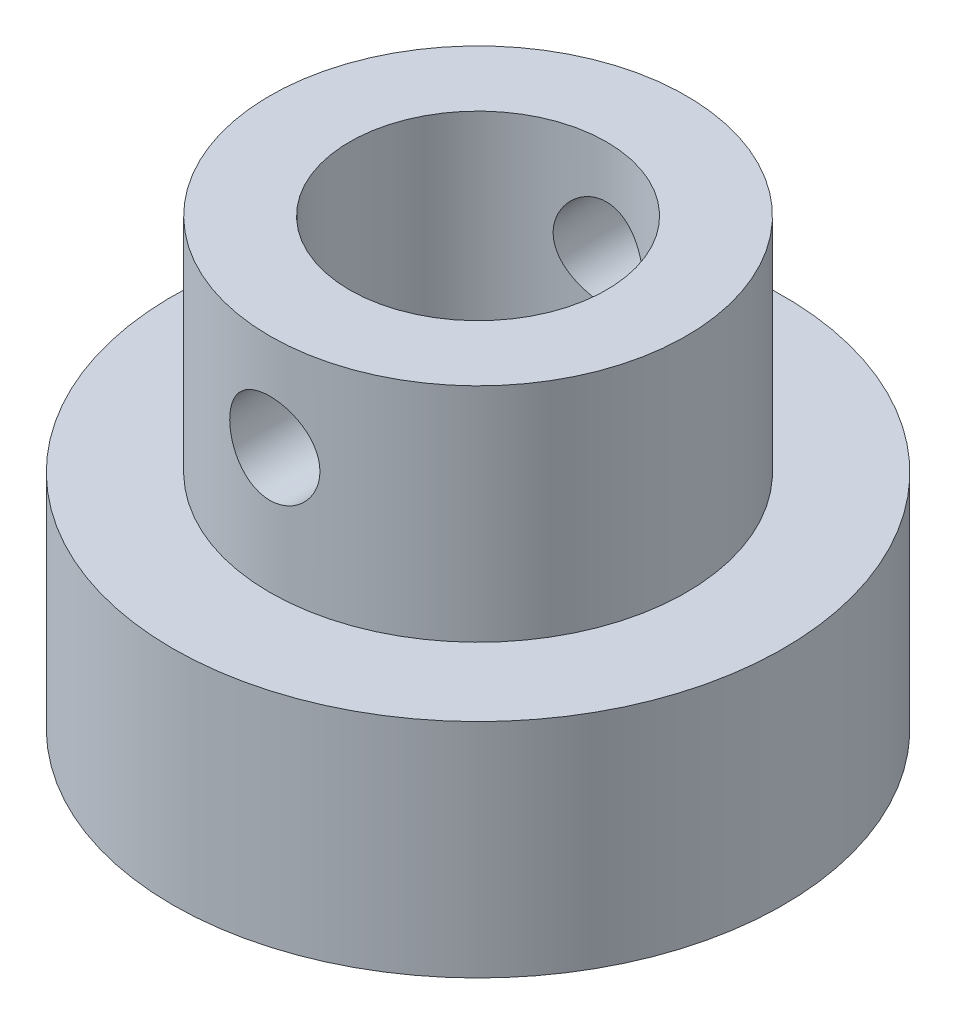
SolidWorks part; units mm, degrees
ref_plane "Front Plane" through (0, 0, 0) normal (0, 0, 1) x (1, 0, 0)
ref_plane "Top Plane" through (0, 0, 0) normal (0, 1, 0) x (1, 0, 0)
ref_plane "Right Plane" through (0, 0, 0) normal (1, 0, 0) x (0, 0, -1)
sketch "Sketch1" plane through (0, 0, 0) normal (0, 1, 0) x (1, 0, 0)
  circle A0 centre (0, 0) radius 11
  dimension "D1" = 22
extrude "Boss-Extrude1" add sketch "Sketch1" along normal blind 8
sketch "Sketch2" plane through (0, 8, 0) normal (0, 1, 0) x (1, 0, 0)
  circle A0 centre (0, 0) radius 7.5
  dimension "D1" = 15
extrude "Boss-Extrude2" add sketch "Sketch2" along normal blind 8 contours A0
sketch "Sketch3" plane through (0, 16, 0) normal (0, 1, 0) x (1, 0, 0)
  circle A0 centre (0, 0) radius 4.625
  dimension "D1" = 9.25
extrude "Cut-Extrude1" cut sketch "Sketch3" against normal blind 8
hole_wizard "Ø3.0mm Dowel Hole1" positions "Sketch6" profile "Sketch7" hole size "Ø3.0" standard "ANSI Metric"
sketch "Sketch6" plane through (0, 0, 0) normal (0, -1, 0) x (-1, 0, 0)
  line L0 (0, 0) -> (-8, 0) construction
  point P0 (-8, 0)
  point P8 (-8, 0.6555)
  point P9 (-0.2323, 0.0776)
  point P10 (0, 0)
  point P11 (-8, -0.6618)
  dimension "D1" = 8
  dimension "D2" = 0
sketch "Sketch7" plane through (8, 0, 0) normal (1, 0, 0) x (0, 0, -1)
  line L0 (0, 0) -> (0, 6.9013)
  line L1 (0, 6.9013) -> (1.5, 6)
  line L2 (1.5, 6) -> (1.5, 0.4828)
  line L3 (1.5, 0.4828) -> (1.7, 0)
  line L5 (1.7, 0) -> (0, 0)
  line L6 (-1.5, 0.4828) -> (-1.7, 0) construction
  line L10 (0, 6.9013) -> (-1.5, 6) construction
  line L11 (0, -6.35) -> (0, 107.95) construction
  dimension "Hole Dia." = 3
  dimension "Hole Depth" = 6
  dimension "Near C'Sink Dia." = 3.4
  dimension "Near C'Sink Angle" = 45
  dimension "Drill Angle" = 118
pattern_circular "CirPattern1" count 4 every 90 about axis through (0, 0, 0) along (0, 1, 0) of "Ø3.0mm Dowel Hole1"
hole_wizard "Ø5.0mm Dowel Hole1" positions "Sketch8" profile "Sketch10" hole size "Ø5.0" standard "ANSI Metric"
sketch "Sketch8" plane through (0, 0, 0) normal (0, 0, 1) x (1, 0, 0)
  line L0 (7.5, 16) -> (-7.5, 16) construction
  point P0 (0, 12.5)
  dimension "D1" = 3.5
sketch "Sketch10" plane through (0, 12.5, 0) normal (1, 0, 0) x (0, 1, 0)
  line L0 (0, 0) -> (0, 11)
  line L1 (0, 11) -> (1.625, 11)
  line L2 (1.625, 11) -> (1.625, 0)
  line L5 (1.625, 0) -> (0, 0)
  line L11 (0, -6.35) -> (0, 107.95) construction
  dimension "Thru Hole Dia." = 3.25
  dimension "Thru Hole Depth" = 11
mirror "Mirror1" about plane through (0, 0, 0) normal (0, 0, 1) of "Ø5.0mm Dowel Hole1"
